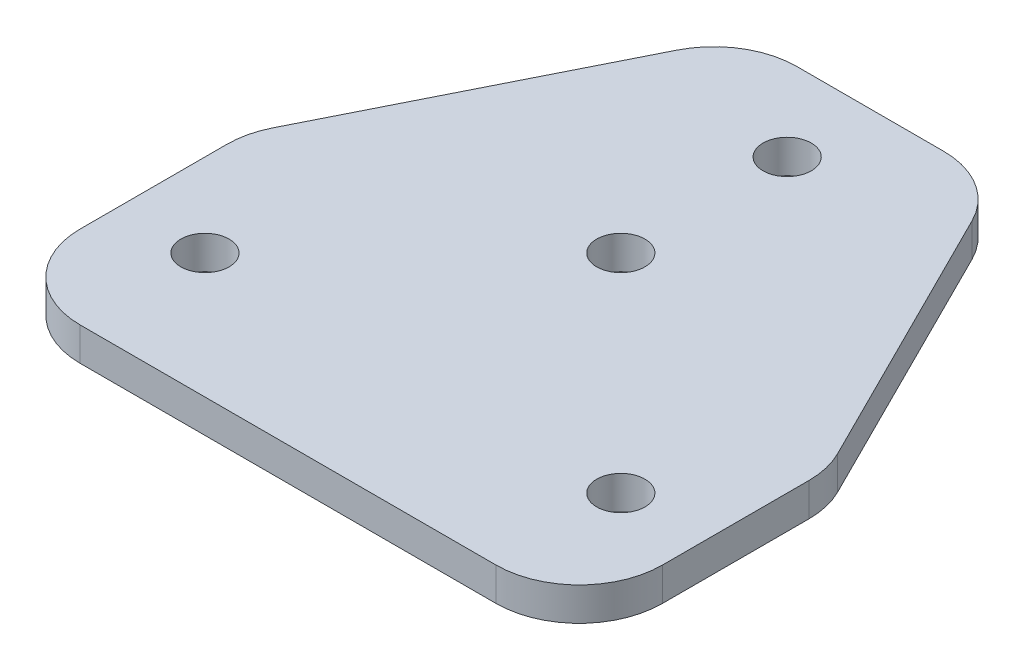
SolidWorks part; units mm, degrees
material "Thornel Mat VMA"
ref_plane "前视基准面" through (0, 0, 0) normal (0, 0, 1) x (1, 0, 0)
ref_plane "上视基准面" through (0, 0, 0) normal (0, 1, 0) x (1, 0, 0)
ref_plane "右视基准面" through (0, 0, 0) normal (1, 0, 0) x (0, 0, -1)
other "Configuration Table"
sketch "草图1" plane through (0, 0, 0) normal (0, 1, 0) x (1, 0, 0)
  line L0 (0, 66.3235) -> (0, -51.7157) construction
  line L1 (-17.5, -7.5) -> (17.5, -7.5) construction
  line L2 (-17.5, -7.5) -> (-17.5, 7.5) construction
  line L3 (-17.5, 7.5) -> (17.5, 7.5) construction
  line L4 (17.5, -7.5) -> (17.5, 7.5) construction
  line L5 (-17.5, -7.5) -> (17.5, 7.5) construction
  line L6 (-17.5, 7.5) -> (17.5, -7.5) construction
  line L7 (-7.5, -7.5) -> (7.5, -7.5) construction
  line L8 (-7.5, -7.5) -> (-7.5, 27.5) construction
  line L9 (-7.5, 27.5) -> (7.5, 27.5) construction
  line L10 (7.5, -7.5) -> (7.5, 27.5) construction
  line L11 (-60.9314, 0) -> (80.4412, 0) construction
  line L12 (-17.5, -7.5) -> (-17.5, 7.5)
  line L13 (-17.5, 7.5) -> (-7.5, 27.5)
  line L14 (-7.5, 27.5) -> (7.5, 27.5)
  line L15 (7.5, 27.5) -> (17.5, 7.5)
  line L16 (17.5, 7.5) -> (17.5, -7.5)
  line L17 (17.5, -7.5) -> (-17.5, -7.5)
  circle A0 centre (12.5, 0) radius 1.45
  circle A1 centre (0, 12.5) radius 1.45
  circle A2 centre (0, 22.5) radius 1.45
  circle A3 centre (-12.5, 0) radius 1.45
  point P0 (0, 0)
  dimension "D5" = 10
  dimension "D6" = 5
  dimension "D7" = 25
  dimension "D8" = 5
  dimension "D9" = 2.9
  dimension "D1" = 15
  dimension "D2" = 7.5
  dimension "D3" = 7.5
  dimension "D4" = 5
extrude "凸台-拉伸1" add sketch "草图1" along normal blind 2
fillet "圆角1" radius 5 6 edges at (-17.5, 1, 7.5) (-17.5, 1, -7.5) (-7.5, 1, -27.5) (7.5, 1, -27.5) (17.5, 1, -7.5) (17.5, 1, 7.5)
